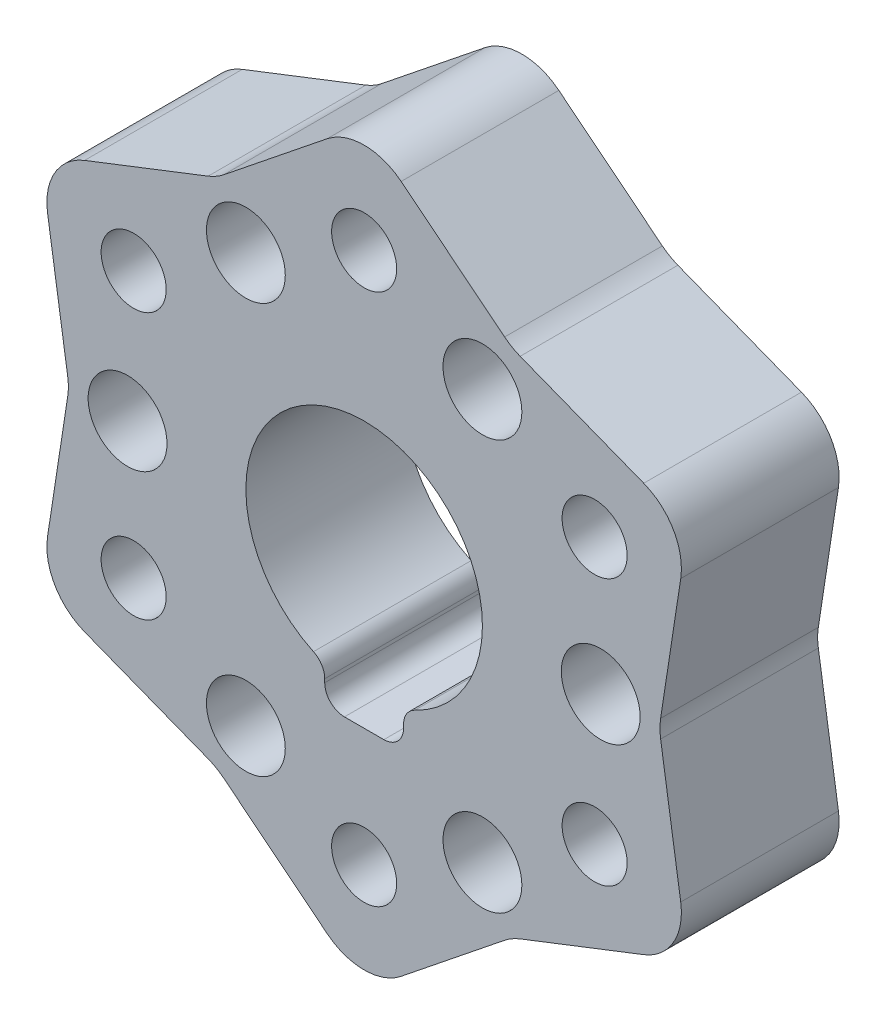
SolidWorks part; units mm, degrees
material "6061 合金"
ref_plane "前视基准面" through (0, 0, 0) normal (0, 0, 1) x (1, 0, 0)
ref_plane "上视基准面" through (0, 0, 0) normal (0, 1, 0) x (1, 0, 0)
ref_plane "右视基准面" through (0, 0, 0) normal (1, 0, 0) x (0, 0, -1)
other "Configuration Table"
sketch "草图2" plane through (0, 0, 0) normal (0, 0, 1) x (1, 0, 0)
  line L0 (0, 0) -> (6, 10.3923) construction
  line L1 (0, 0) -> (0, 12) construction
  line L2 (0, 18.9637) -> (7.4846, 12.9637)
  line L3 (16.423, 9.4818) -> (7.4846, 12.9637)
  line L4 (0, 18.9637) -> (-7.4846, 12.9637)
  line L5 (16.423, 9.4818) -> (14.9692, 0)
  line L6 (16.423, -9.4818) -> (14.9692, 0)
  line L7 (16.423, -9.4818) -> (7.4846, -12.9637)
  line L8 (0, -18.9637) -> (7.4846, -12.9637)
  line L9 (0, -18.9637) -> (-7.4846, -12.9637)
  line L10 (-16.423, -9.4818) -> (-7.4846, -12.9637)
  line L11 (-16.423, -9.4818) -> (-14.9692, 0)
  line L12 (-16.423, 9.4818) -> (-14.9692, 0)
  line L13 (-16.423, 9.4818) -> (-7.4846, 12.9637)
  line L15 (0, -7.5) -> (2, -7.5)
  line L16 (2, -7.5) -> (2, -5.6569)
  line L17 (0, -7.5) -> (-2, -7.5)
  line L18 (-2, -7.5) -> (-2, -5.6569)
  circle A0 centre (0, 0) radius 13.5 construction
  circle A1 centre (0, 13.5) radius 1.65
  circle A2 centre (11.6913, 6.75) radius 1.65
  circle A3 centre (11.6913, -6.75) radius 1.65
  circle A4 centre (0, -13.5) radius 1.65
  circle A5 centre (-11.6913, -6.75) radius 1.65
  circle A6 centre (-11.6913, 6.75) radius 1.65
  circle A7 centre (0, 0) radius 12 construction
  circle A8 centre (6, 10.3923) radius 2
  circle A9 centre (12, 0) radius 2
  circle A10 centre (6, -10.3923) radius 2
  circle A11 centre (-6, -10.3923) radius 2
  circle A12 centre (-12, 0) radius 2
  circle A13 centre (-6, 10.3923) radius 2
  arc A14 (2, -5.6569) -> (-2, -5.6569) centre (0, 0) ccw
  point P17 (0, 0)
  point P33 (0, 0)
  point P52 (0, 0)
  dimension "D1" = 6
  dimension "D2" = 3.3
  dimension "D3" = 30
  dimension "D4" = 4
  dimension "D8" = 12
  dimension "D12" = 27
  dimension "D6" = 6
  dimension "D7" = 6
  dimension "D9" = 7.5
  dimension "D10" = 2
  dimension "D11" = 2
  dimension "D5" = 6
extrude "凸台-拉伸1" add sketch "草图2" along normal blind 8
fillet "圆角1" radius 3 12 edges at (7.4846, 12.9637, 4) (16.423, 9.4818, 4) (14.9692, 0, 4) (16.423, -9.4818, 4) (7.4846, -12.9637, 4) (0, -18.9637, 4) (-7.4846, -12.9637, 4) (-16.423, -9.4818, 4) (-14.9692, 0, 4) (-16.423, 9.4818, 4) (-7.4846, 12.9637, 4) (0, 18.9637, 4)
fillet "圆角2" radius 1 4 edges at (2, -7.5, 4) (2, -5.6569, 4) (-2, -7.5, 4) (-2, -5.6569, 4)
